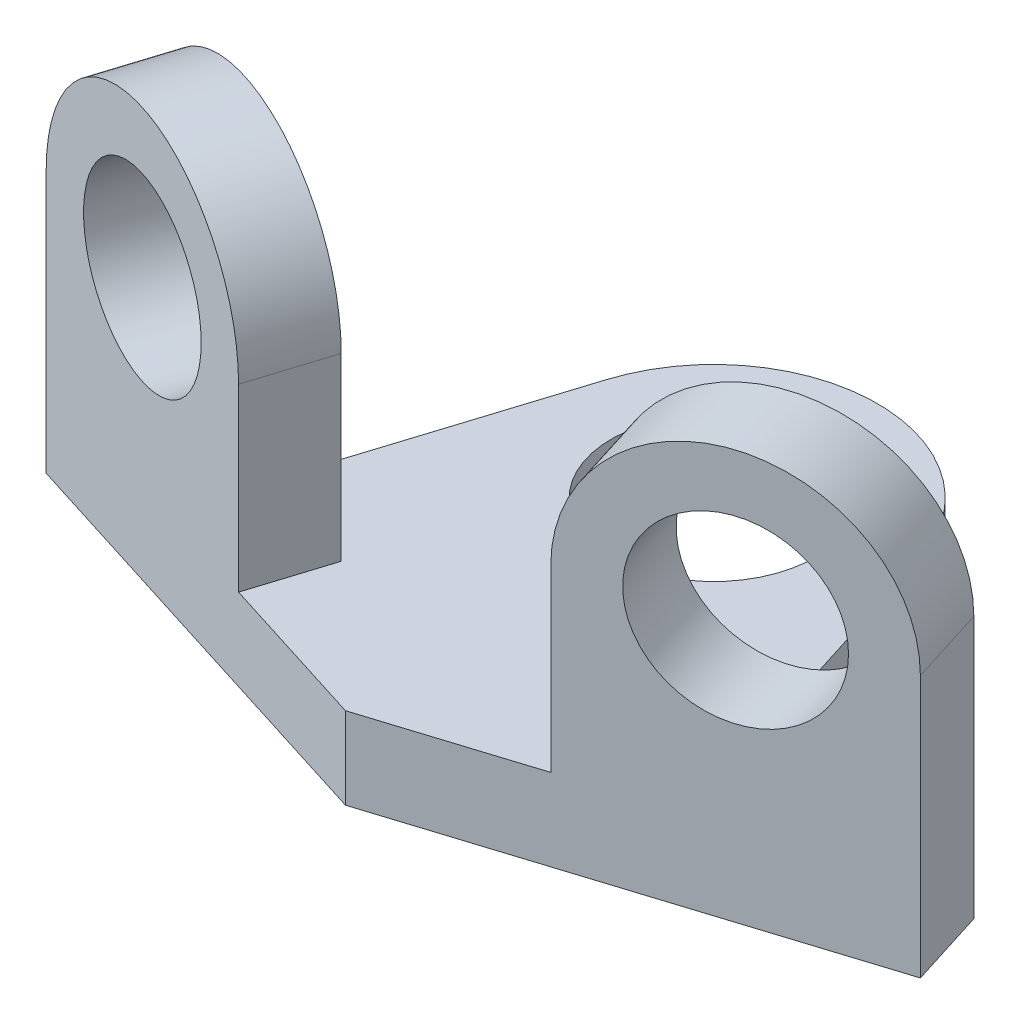
SolidWorks part; units mm, degrees
ref_plane "Front Plane" through (0, 0, 0) normal (0, 0, 1) x (1, 0, 0)
ref_plane "Top Plane" through (0, 0, 0) normal (0, 1, 0) x (1, 0, 0)
ref_plane "Right Plane" through (0, 0, 0) normal (1, 0, 0) x (0, 0, -1)
sketch "Sketch1" plane through (0, 0, 0) normal (0, 1, 0) x (1, 0, 0)
  line L0 (16.0673, 15.5513) -> (19.0743, 6.0141)
  line L1 (0, 0) -> (-53.4081, 16.8395)
  line L2 (0, 0) -> (53.4081, 16.8395)
  line L3 (53.4081, 16.8395) -> (50.4011, 26.3767)
  line L4 (0, 0) -> (0, 45)
  line L5 (0, 45) -> (0, 65) construction
  line L6 (50.4011, 26.3767) -> (16.0673, 15.5513)
  line L7 (19.0743, 51.0141) -> (31.9798, 10.0832)
  line L8 (-19.0743, 51.0141) -> (-31.9798, 10.0832)
  line L9 (19.0743, 51.0141) -> (28.8006, 20.1664)
  line L10 (-53.4081, 16.8395) -> (-50.4011, 26.3767)
  line L11 (-50.4011, 26.3767) -> (-16.0673, 15.5513)
  line L12 (-16.0673, 15.5513) -> (-19.0743, 6.0141)
  circle A0 centre (0, 45) radius 12.5
  circle A1 centre (0, 45) radius 20
  dimension "D3" = 35
  dimension "D4" = 40
  dimension "D1" = 25
  dimension "D2" = 56
extrude "Boss-Extrude1" add sketch "Sketch1" along normal blind 10 contours L5 A0 L4 A1 | A0 L5 A1 L4 | A1 L8 L11 L12 L1 L4 | L12 L11 L8 L1 | L11 L10 L1 L8 | A1 L4 L2 L0 L6 L7 | L7 L6 L0 L2 | L6 L7 L2 L3
sketch "Sketch2" plane through (0, 0, 0) normal (0.3007, 0, 0.9537) x (0.9537, 0, -0.3007)
  line L0 (56, 0) -> (56, 32)
  line L3 (20, 32) -> (20, 0)
  line L4 (0, 0) -> (56, 0) construction
  line L5 (20, 0) -> (56, 0)
  circle A0 centre (38, 32) radius 18
  circle A1 centre (38, 32) radius 11
  line M1 (0, 0) -> (56, 0)
  line M2 (56, 0) -> (56, 10)
  line M3 (56, 10) -> (0, 10)
  dimension "D1" = 32
extrude "Boss-Extrude2" add sketch "Sketch2" against normal blind 10 contours A0 A1 | A0 L3 L0 M3 | L3 M3 M1 M2
sketch "Sketch3" plane through (0, 0, 0) normal (-0.3007, 0, 0.9537) x (0.9537, 0, 0.3007)
  line L0 (-56, 0) -> (-56, 32)
  line L2 (-20, 32) -> (-20, 0)
  line L3 (0, 0) -> (-56, 0) construction
  line L4 (-20, 0) -> (-56, 0)
  circle A0 centre (-38, 32) radius 18
  circle A1 centre (-38, 32) radius 11
  line M2 (-56, 0) -> (0, 0)
  line M4 (0, 10) -> (-56, 10)
  line M5 (-56, 10) -> (-56, 0)
  dimension "D1" = 32
extrude "Boss-Extrude3" add sketch "Sketch3" against normal blind 10 contours A0 A1 | A0 L0 L2 M4 | L2 M4 M5 M2
